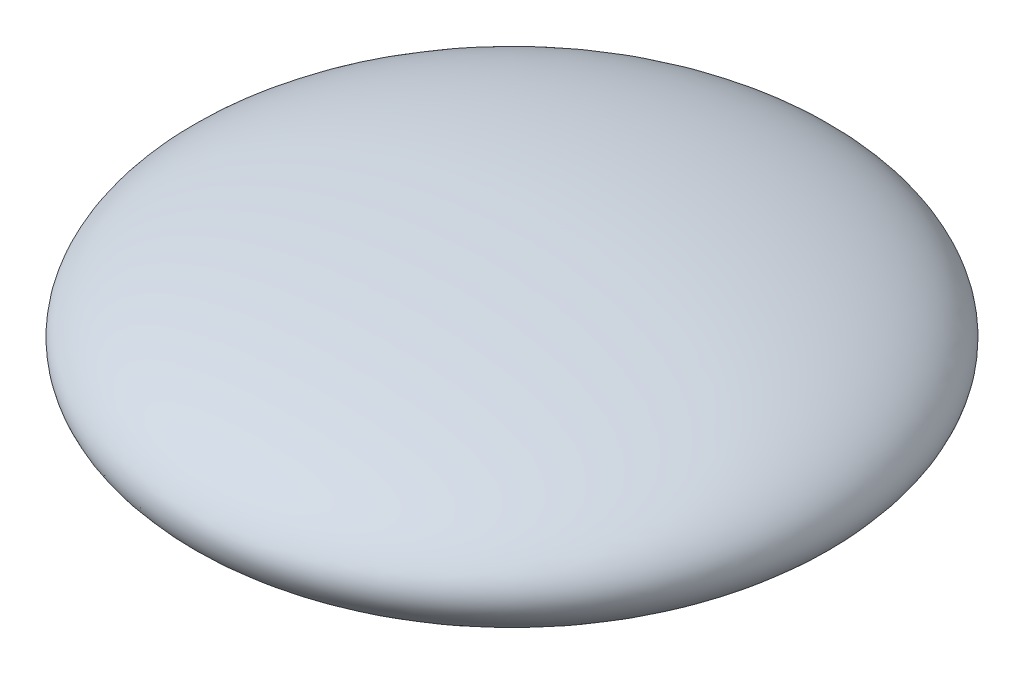
SolidWorks part; units mm, degrees
ref_plane "Front Plane" through (0, 0, 0) normal (0, 0, 1) x (1, 0, 0)
ref_plane "Top Plane" through (0, 0, 0) normal (0, 1, 0) x (1, 0, 0)
ref_plane "Right Plane" through (0, 0, 0) normal (1, 0, 0) x (0, 0, -1)
sketch "Sketch1" plane through (0, 0, 0) normal (0, 0, 1) x (1, 0, 0)
  line L0 (0, -55) -> (0, 55) construction
  line L1 (0, 14.3) -> (0, 0)
  line L2 (0, 0) -> (14.85, 0)
  line L3 (14.85, 0) -> (21.733, 3.5)
  line L4 (55, 0) -> (-55, 0) construction
  ellipse E0 centre (0, 7.0723) end of major axis (25, 7.0723) minor radius 7.2277 (21.733, 3.5) -> (0, 14.3) ccw
  dimension "D1" = 14.3
  dimension "D2" = 25
  dimension "D3" = 14.85
  dimension "D4" = 3.5
revolve "Revolve1" add sketch "Sketch1" angle 360 about L1
